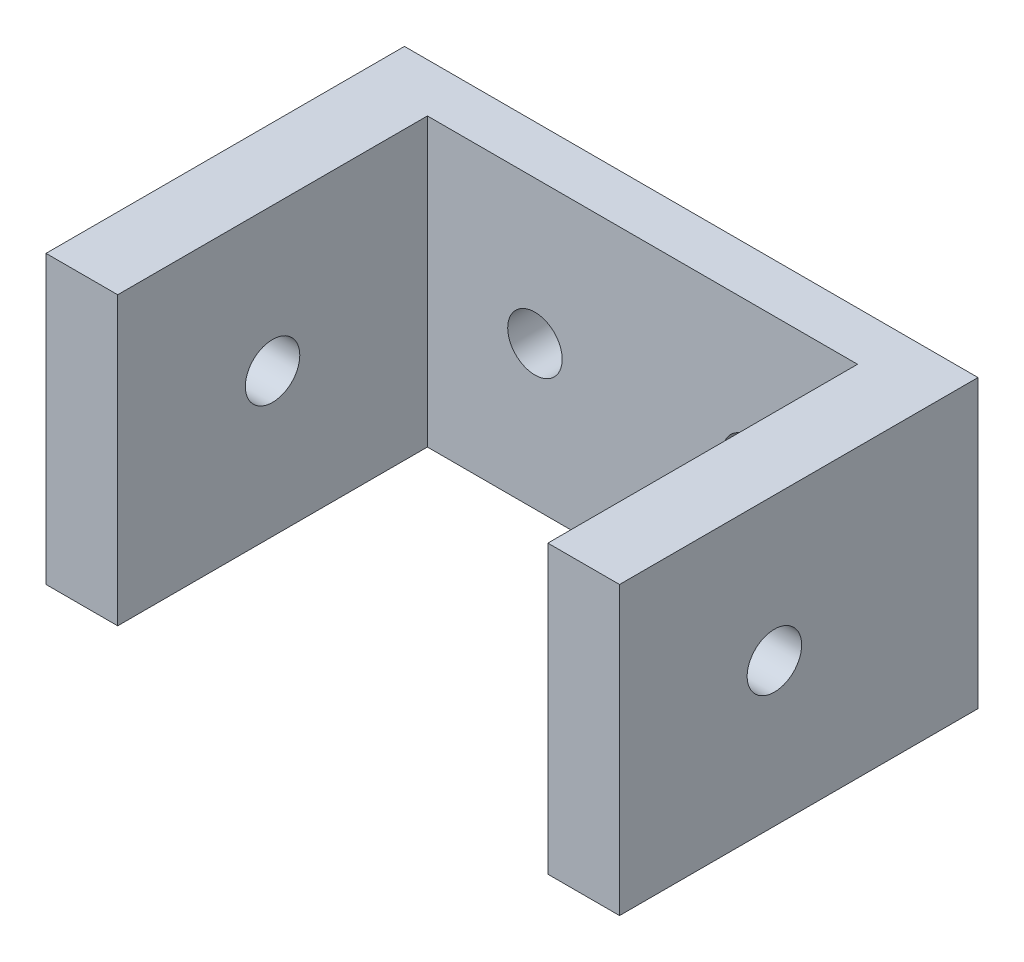
SolidWorks part; units mm, degrees
material "6061-T6 (SS)"
ref_plane "Front Plane" through (0, 0, 0) normal (0, 0, 1) x (1, 0, 0)
ref_plane "Top Plane" through (0, 0, 0) normal (0, 1, 0) x (1, 0, 0)
ref_plane "Right Plane" through (0, 0, 0) normal (1, 0, 0) x (0, 0, -1)
sketch "Sketch1" plane through (0, 0, 0) normal (0, 0, 1) x (1, 0, 0)
  line L1 (-25.4, -12.7) -> (25.4, -12.7)
  line L2 (-25.4, -12.7) -> (-25.4, 12.7)
  line L3 (-25.4, 12.7) -> (25.4, 12.7)
  line L4 (25.4, -12.7) -> (25.4, 12.7)
  line L5 (-25.4, -12.7) -> (25.4, 12.7) construction
  line L6 (-25.4, 12.7) -> (25.4, -12.7) construction
  point P0 (0, 0)
  dimension "D1" = 50.8
  dimension "D2" = 25.4
extrude "Boss-Extrude1" add sketch "Sketch1" along normal blind 4.318
sketch "Sketch2" plane through (0, 0, 4.318) normal (0, 0, 1) x (1, 0, 0)
  line L0 (-25.4, -12.7) -> (25.4, -12.7) construction
  line L1 (-25.4, 12.7) -> (-19.05, 12.7)
  line L2 (-25.4, 12.7) -> (-25.4, -12.7)
  line L3 (-25.4, -12.7) -> (-19.05, -12.7)
  line L4 (-19.05, 12.7) -> (-19.05, -12.7)
  line L6 (25.4, 12.7) -> (19.05, 12.7)
  line L7 (25.4, 12.7) -> (25.4, -12.7)
  line L8 (25.4, -12.7) -> (19.05, -12.7)
  line L9 (19.05, 12.7) -> (19.05, -12.7)
  dimension "D1" = 38.1
extrude "Boss-Extrude2" add sketch "Sketch2" along normal blind 27.432
sketch "Sketch4" plane through (0, 0, 0) normal (0, 0, -1) x (-1, 0, 0)
  line L0 (25.4, 0) -> (-25.4, 0) construction
  line L1 (25.4, 12.7) -> (25.4, -12.7) construction
  line L2 (-25.4, -12.7) -> (-25.4, 12.7) construction
  circle A0 centre (-9.525, 0) radius 2.413
  circle A1 centre (9.525, 0) radius 2.413
  dimension "D1" = 4.826
  dimension "D2" = 15.875
  dimension "D3" = 15.875
extrude "Cut-Extrude1" cut sketch "Sketch4" against normal blind 4.318
sketch "Sketch5" plane through (-19.05, 0, 0) normal (1, 0, 0) x (0, 0, -1)
  line L0 (-31.75, 12.7) -> (-4.318, -12.7) construction
  line L1 (-4.318, 12.7) -> (-31.75, -12.7) construction
  circle A0 centre (-18.034, 0) radius 2.413
  dimension "D1" = 4.826
extrude "Cut-Extrude2" cut sketch "Sketch5" against normal through all and the other way through all
